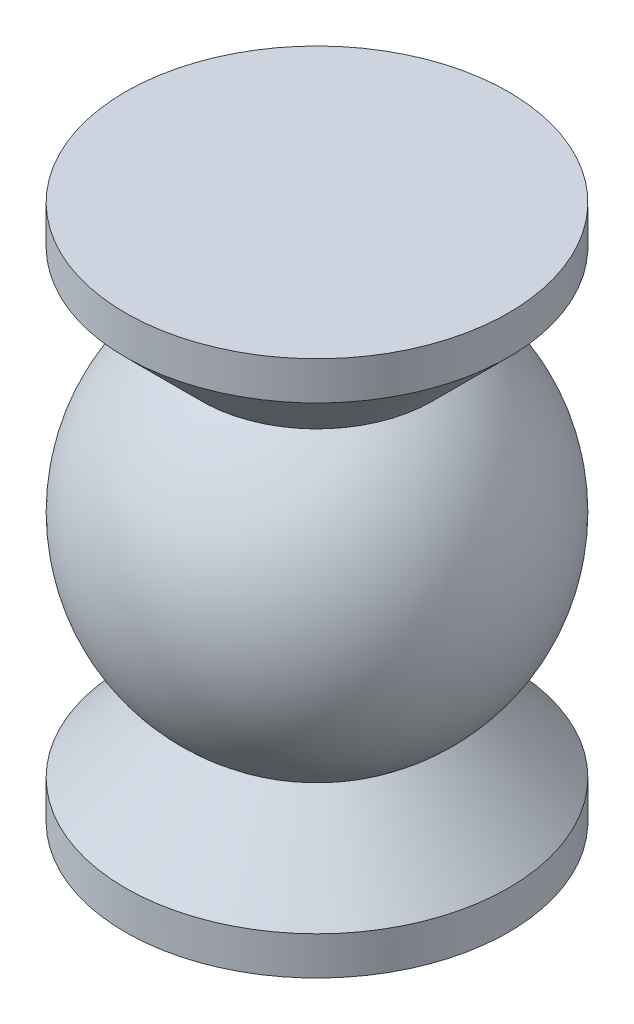
SolidWorks part; units mm, degrees
ref_plane "前视基准面" through (0, 0, 0) normal (0, 0, 1) x (1, 0, 0)
ref_plane "上视基准面" through (0, 0, 0) normal (0, 1, 0) x (1, 0, 0)
ref_plane "右视基准面" through (0, 0, 0) normal (1, 0, 0) x (0, 0, -1)
sketch "草图1" plane through (0, 0, 0) normal (0, 0, 1) x (1, 0, 0)
  line L0 (15, 20) -> (15, -20) construction
  line L1 (15, 20) -> (25, 30)
  line L2 (25, 30) -> (25, 35)
  line L3 (25, 35) -> (0, 35)
  line L4 (0, 35) -> (0, -35)
  line L5 (0, -35) -> (25, -35)
  line L6 (25, -35) -> (25, -30)
  line L7 (25, -30) -> (15, -20)
  arc A0 (15, -20) -> (15, 20) centre (0, 0) ccw
  dimension "D1" = 50
  dimension "D2" = 40
  dimension "D3" = 25
  dimension "D4" = 25
  dimension "D5" = 35
  dimension "D6" = 35
  dimension "D7" = 5
  dimension "D8" = 5
revolve "旋转1" add sketch "草图1" angle 360 about L4
